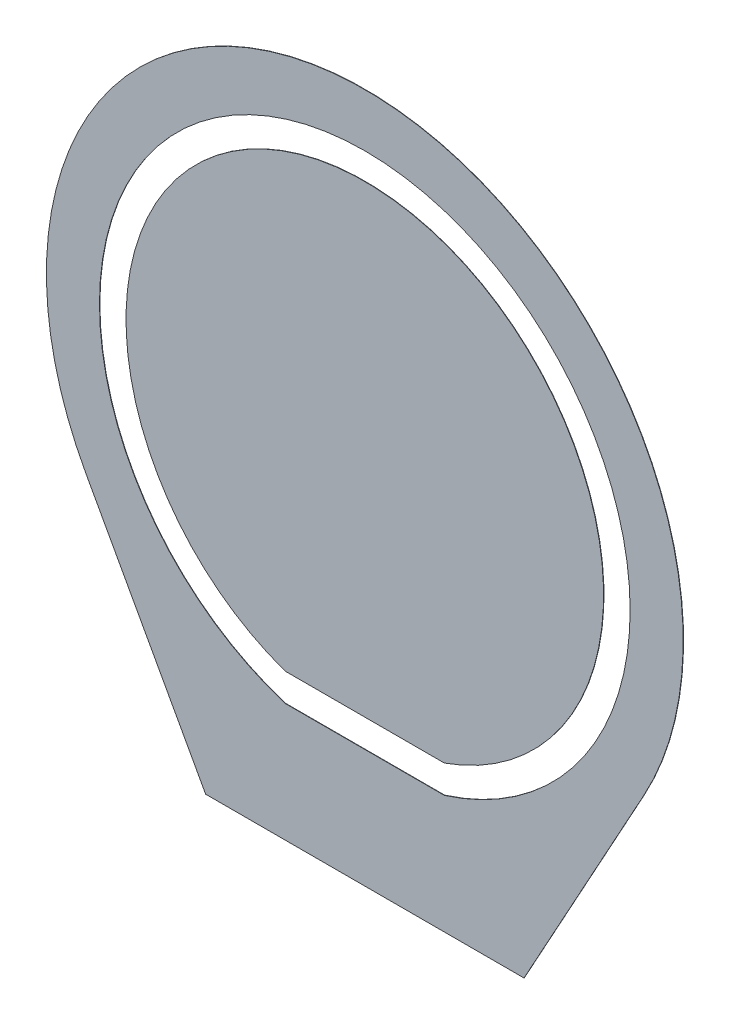
SolidWorks part; units mm, degrees
ref_plane "Plano frontal" through (0, 0, 0) normal (0, 0, 1) x (1, 0, 0)
ref_plane "Plano superior" through (0, 0, 0) normal (0, 1, 0) x (1, 0, 0)
ref_plane "Plano direito" through (0, 0, 0) normal (1, 0, 0) x (0, 0, -1)
sketch "Sketch1" plane through (0, 0, 0) normal (0, 0, 1) x (1, 0, 0)
  line L4 (-7.5, -21.2132) -> (7.5, -21.2132)
  line L8 (-7.5, -23.8485) -> (7.5, -23.8485)
  line L9 (0, -23.8485) -> (0, -35)
  line L10 (-15, -35) -> (15, -35)
  line L12 (-7.5, -23.8485) -> (7.5, -23.8485)
  line L13 (15, -25.6868) -> (15, -25.9808)
  line L14 (-15, -35) -> (-26.2929, -14.4459)
  line L15 (15, -35) -> (26.2929, -14.4459)
  arc A0 (7.5, -21.2132) -> (-7.5, -21.2132) centre (0, 0) ccw
  arc A1 (7.5, -23.8485) -> (-7.5, -23.8485) centre (0, 0) ccw
  arc A2 (26.2929, -14.4459) -> (-26.2929, -14.4459) centre (0, 0) ccw
  point P11 (0, -35)
  point P12 (-56.709, 8.9907)
  dimension "D6" = 50
  dimension "D7" = 60
  dimension "D3" = 2.6353
  dimension "D4" = 11.1515
  dimension "D5" = 30
extrude "Boss-Extrude1" add sketch "Sketch1" along normal blind 0.0356
